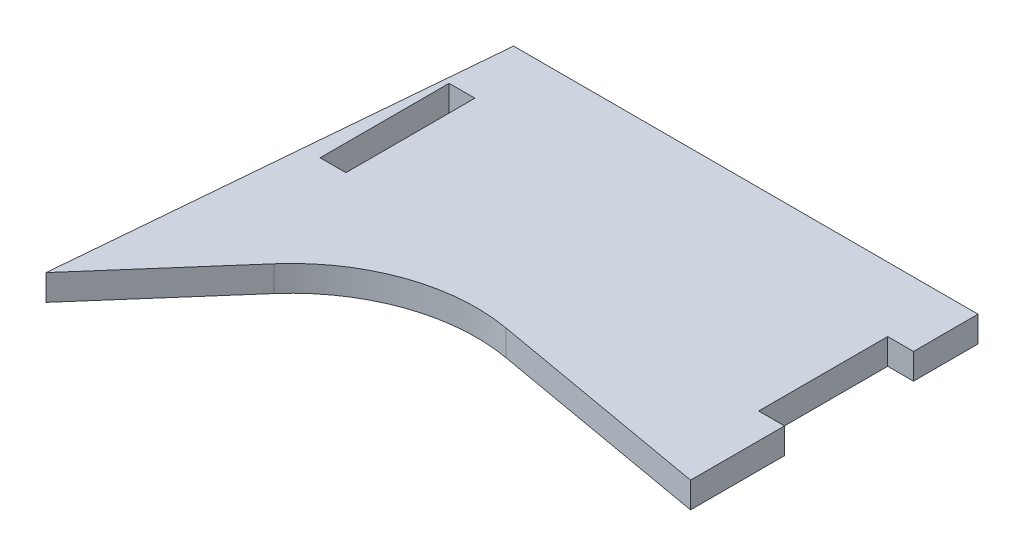
SolidWorks part; units mm, degrees
ref_plane "Front Plane" through (0, 0, 0) normal (0, 0, 1) x (1, 0, 0)
ref_plane "Top Plane" through (0, 0, 0) normal (0, 1, 0) x (1, 0, 0)
ref_plane "Right Plane" through (0, 0, 0) normal (1, 0, 0) x (0, 0, -1)
sketch "Sketch1" plane through (0, 0, 0) normal (0, 1, 0) x (1, 0, 0)
  line L0 (0, 0) -> (-54, 0)
  line L1 (-54, 0) -> (-58.3744, -50)
  line L2 (0, 0) -> (0, -7.5)
  line L3 (-58.3744, -50) -> (-46, -35.8478)
  line L4 (0, -33.4255) -> (-26.0812, -28.8266)
  line L5 (0, -22.5) -> (0, -33.4255)
  line L6 (0, -7.5) -> (-3, -7.5)
  line L8 (0, -22.5) -> (-3, -22.5)
  line L9 (-3, -7.5) -> (-3, -22.5)
  line L11 (-54, -7.5) -> (-51, -7.5)
  line L12 (-54, -7.5) -> (-54, -22.5)
  line L13 (-54, -22.5) -> (-51, -22.5)
  line L14 (-51, -7.5) -> (-51, -22.5)
  line L15 (-54, -7.5) -> (-51, -22.5) construction
  line L16 (-54, -22.5) -> (-51, -7.5) construction
  arc A0 (-46, -35.8478) -> (-26.0812, -28.8266) centre (-29.8147, -50) cw
  point P8 (-52.5, -15)
  point P13 (-3, -15)
  point P14 (0, 0)
  point P36 (-27, 0)
  dimension "D3" = 21.5
  dimension "D1" = 50
  dimension "D2" = 54
  dimension "D4" = 95
  dimension "D5" = 80
  dimension "D6" = 19
  dimension "D7" = 3
  dimension "D8" = 7.5
  dimension "D9" = 15
extrude "Boss-Extrude1" add sketch "Sketch1" along normal blind 3
